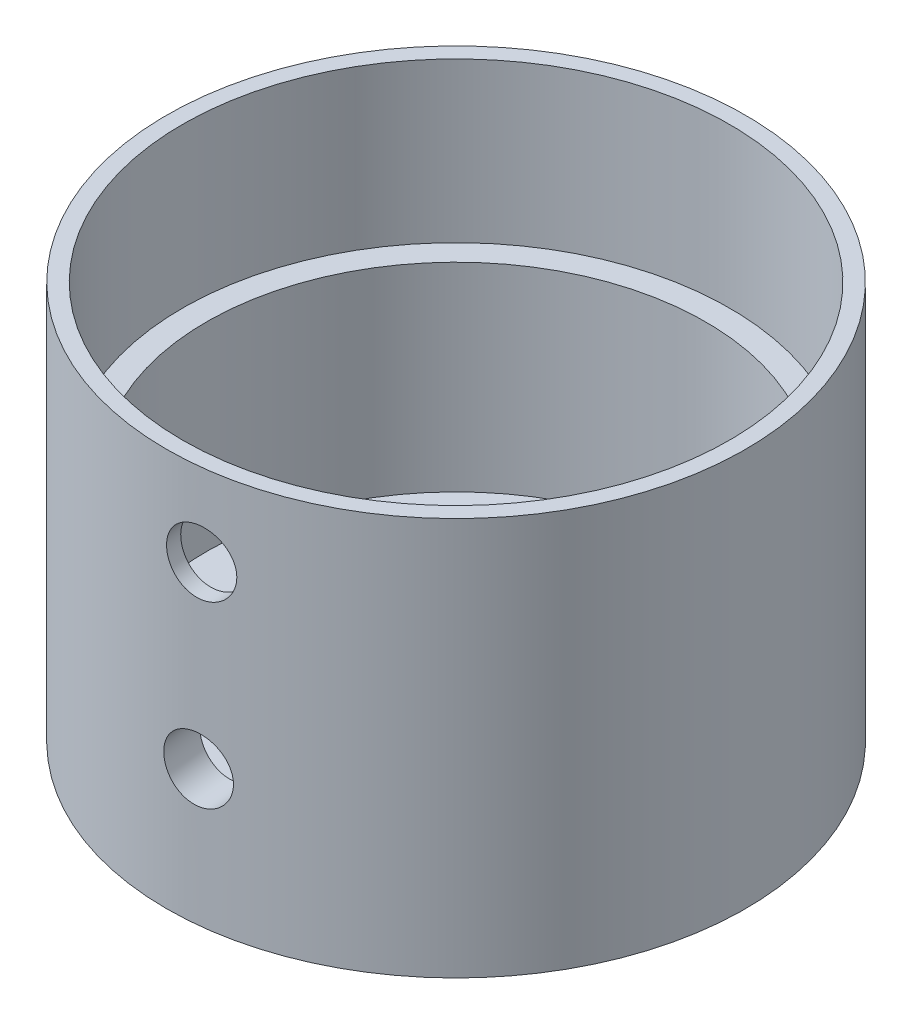
SolidWorks part; units mm, degrees
ref_plane "前基準面" through (0, 0, 0) normal (0, 0, 1) x (1, 0, 0)
ref_plane "上基準面" through (0, 0, 0) normal (0, 1, 0) x (1, 0, 0)
ref_plane "右基準面" through (0, 0, 0) normal (1, 0, 0) x (0, 0, -1)
sketch "草圖6" plane through (0, 0, 0) normal (0, 1, 0) x (1, 0, 0)
  circle A2 centre (0, 0) radius 72.75
  circle A3 centre (0, 0) radius 70.75
  dimension "D1" = 2
  dimension "D3" = 145.5
extrude "填料-伸長16" add sketch "草圖6" along normal blind 100 contours A2
shell "薄殼8" thickness 10
sketch "草圖13" plane through (0, 100, 0) normal (0, 1, 0) x (1, 0, 0)
  circle A0 centre (0, 0) radius 68.75
  circle A1 centre (0, 0) radius 72.75 construction
  circle A2 centre (0, 0) radius 62.75
  dimension "D1" = 4
extrude "除料-伸長5" cut sketch "草圖13" against normal blind 40
hole_wizard "Ø16.0mm 定位孔2" positions "3D草圖2" profile "草圖16" hole size "Ø16.0" standard "JIS"
sketch3d "3D草圖2"
  point P0 (7.2813, 33.876, 72.3847)
  point P3 (7.9851, 79.1792, 72.3104)
sketch "草圖16" plane through (7.2813, 33.876, 72.3847) normal (0, 1, 0) x (0.995, 0, -0.1001)
  line L0 (0, 0) -> (0, 10)
  line L1 (0, 10) -> (8, 10)
  line L2 (8, 10) -> (8, 0)
  line L5 (8, 0) -> (0, 0)
  line L11 (0, -6.35) -> (0, 107.95) construction
  dimension "貫穿孔直徑" = 16
  dimension "貫穿孔深度" = 10
